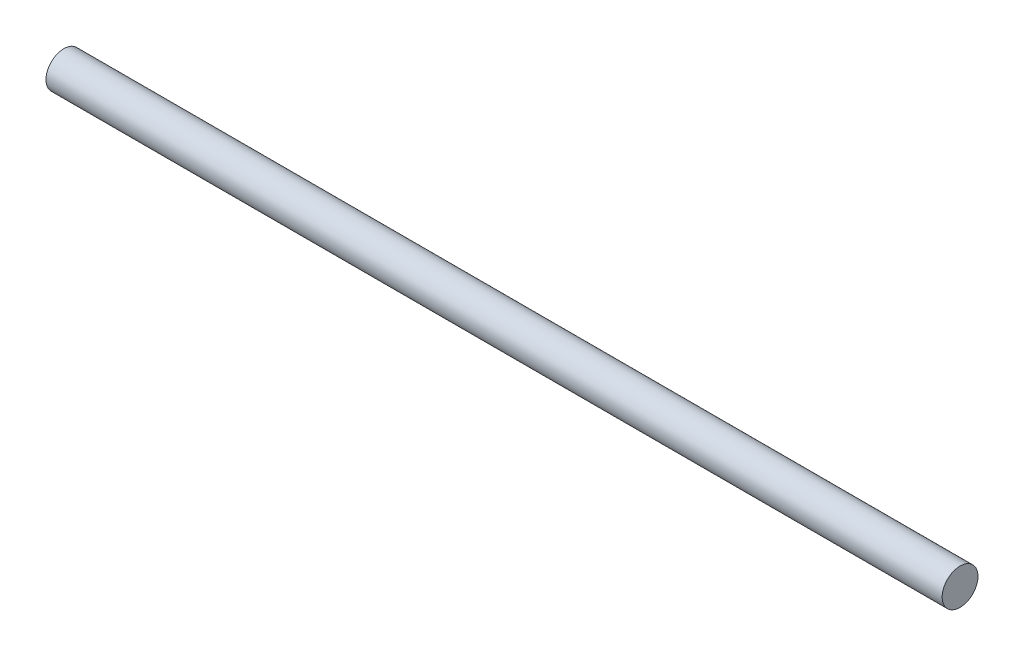
SolidWorks part; units mm, degrees
ref_plane "Alzado" through (0, 0, 0) normal (0, 0, 1) x (1, 0, 0)
ref_plane "Planta" through (0, 0, 0) normal (0, 1, 0) x (1, 0, 0)
ref_plane "Vista lateral" through (0, 0, 0) normal (1, 0, 0) x (0, 0, -1)
sketch "Croquis1" plane through (0, 0, 0) normal (1, 0, 0) x (0, 0, -1)
  circle A0 centre (0, 0) radius 4
  dimension "D1" = 8
extrude "Saliente-Extruir1" add sketch "Croquis1" along normal blind 200
